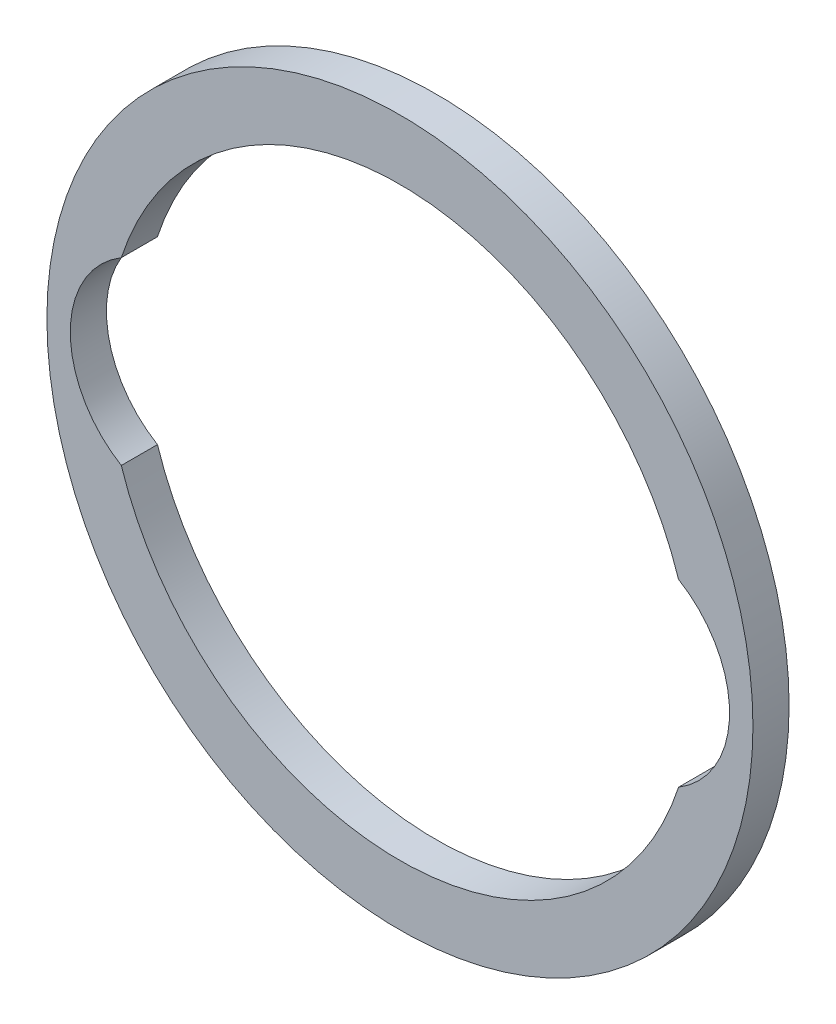
SolidWorks part; units mm, degrees
ref_plane "Přední rovina" through (0, 0, 0) normal (0, 0, 1) x (1, 0, 0)
ref_plane "Horní rovina" through (0, 0, 0) normal (0, 1, 0) x (1, 0, 0)
ref_plane "Pravá rovina" through (0, 0, 0) normal (1, 0, 0) x (0, 0, -1)
sketch "Skica1" plane through (0, 0, 0) normal (0, 0, 1) x (1, 0, 0)
  line L0 (0, 48.6) -> (0, -48.6) construction
  line L1 (-10, 48.6) -> (-10, -48.6)
  arc A0 (-46.2486, -14.9342) -> (46.2486, -14.9342) centre (0, 0) ccw
  arc A1 (46.2486, -14.9342) -> (46.2476, 14.9373) centre (37.3215, 0.0012) ccw
  arc A2 (-46.2486, -14.9342) -> (-46.2476, 14.9373) centre (-37.3215, 0.0012) cw
  arc A3 (46.2476, 14.9373) -> (-46.2476, 14.9373) centre (0, 0) ccw
  arc A4 (54.6071, 21.2608) -> (-54.6071, 21.2608) centre (0, 0) cw
  arc A6 (54.6071, 21.2608) -> (-54.6071, 21.2608) centre (0, 0) ccw
  arc A8 (54.6086, -21.2571) -> (54.6071, 21.2608) centre (37.3215, 0.0012) ccw construction
  arc A9 (-54.6086, -21.2571) -> (-54.6071, 21.2608) centre (-37.3215, 0.0012) cw construction
  arc A10 (-54.6086, -21.2571) -> (54.6086, -21.2571) centre (0, 0) ccw construction
  dimension "D1" = 97.2
  dimension "D2" = 6.1215
  dimension "D3" = 34.8
  dimension "D4" = 10
extrude "Přidat vysunutím1" add sketch "Skica1" along normal blind 6
